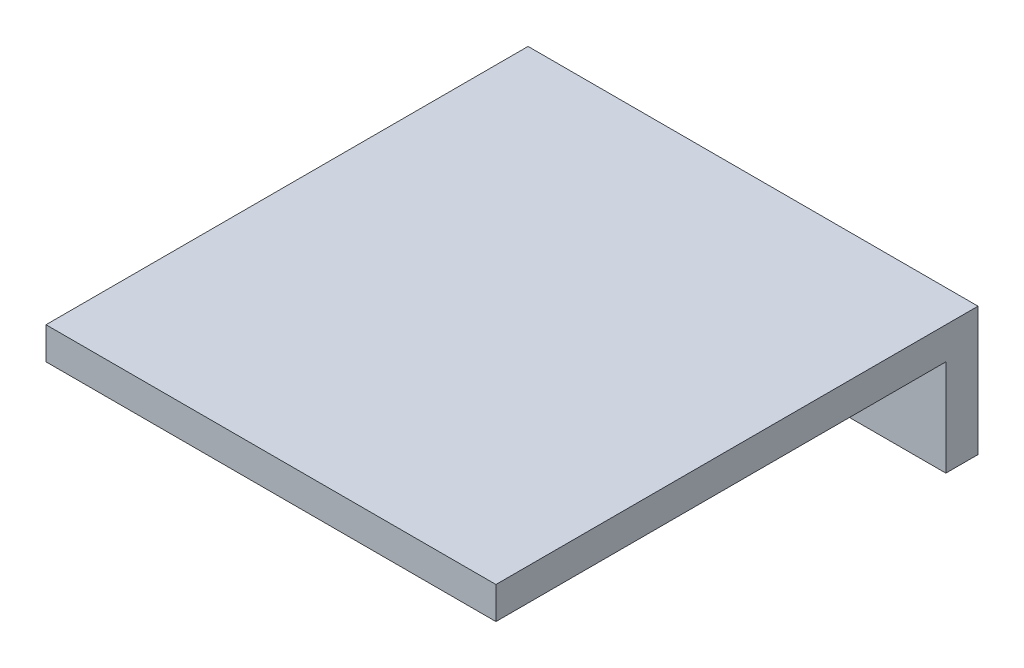
SolidWorks part; units mm, degrees
ref_plane "Plan de face" through (0, 0, 0) normal (0, 0, 1) x (1, 0, 0)
ref_plane "Plan de dessus" through (0, 0, 0) normal (0, 1, 0) x (1, 0, 0)
ref_plane "Plan de droite" through (0, 0, 0) normal (1, 0, 0) x (0, 0, -1)
sketch "Esquisse1" plane through (0, 0, 0) normal (0, 0, 1) x (1, 0, 0)
  line L1 (0, 0) -> (-70, 0)
  line L2 (0, 0) -> (0, 20)
  line L3 (0, 20) -> (-70, 20)
  line L4 (-70, 0) -> (-70, 20)
  dimension "D1" = 20
  dimension "D2" = 70
extrude "Boss.-Extru.1" add sketch "Esquisse1" along normal blind 5
sketch "Esquisse2" plane through (0, 0, 5) normal (0, 0, 1) x (1, 0, 0)
  line L0 (0, 0) -> (0, 20) construction
  line L1 (-70, 20) -> (0, 20)
  line L2 (-70, 20) -> (-70, 15)
  line L3 (-70, 15) -> (0, 15)
  line L4 (0, 20) -> (0, 15)
  dimension "D1" = 5
extrude "Boss.-Extru.2" add sketch "Esquisse2" along normal blind 70
sketch "Esquisse3" plane through (0, 0, 0) normal (0, 0, -1) x (-1, 0, 0)
  line L0 (35, 0) -> (35, 22.9097) construction
  line L1 (70, 0) -> (0, 0) construction
  circle A0 centre (35, 3.2676) radius 1.5
  dimension "D1" = 3
extrude "Enlèv. mat.-Extru.1" cut sketch "Esquisse3" against normal blind 60
